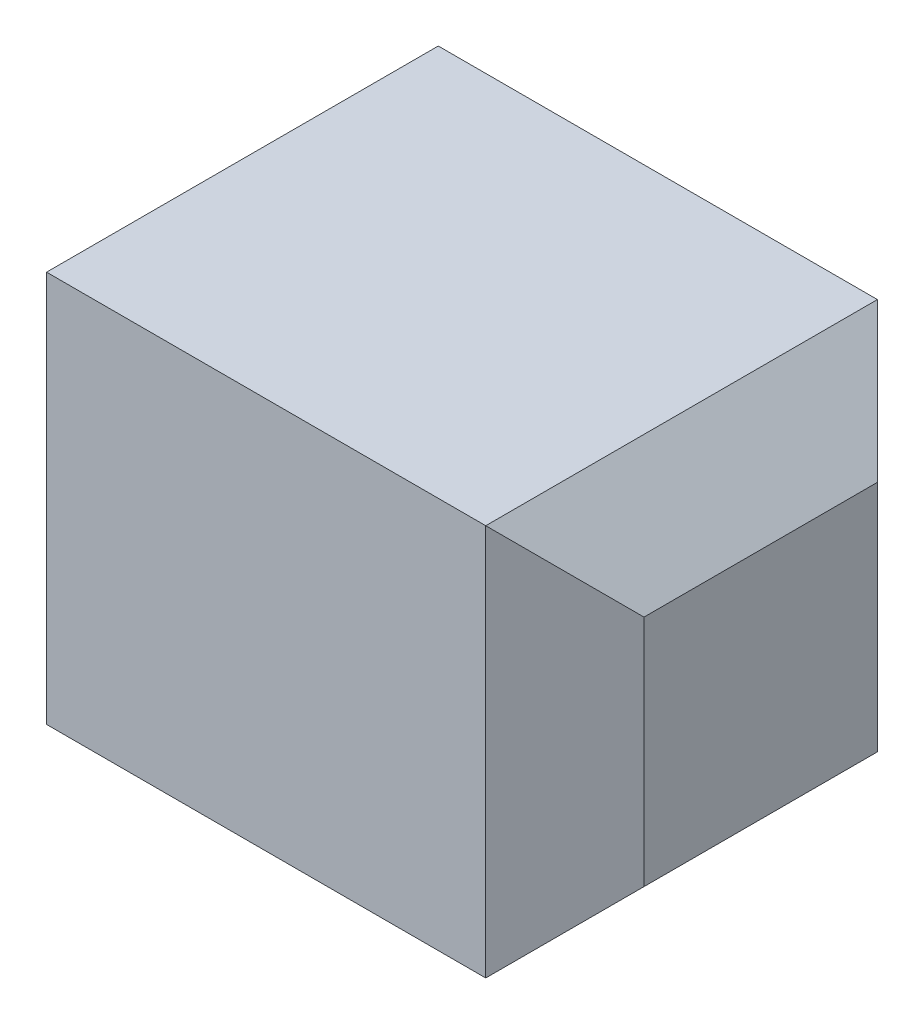
SolidWorks part; units mm, degrees
ref_plane "Front Plane" through (0, 0, 0) normal (0, 0, 1) x (1, 0, 0)
ref_plane "Top Plane" through (0, 0, 0) normal (0, 1, 0) x (1, 0, 0)
ref_plane "Right Plane" through (0, 0, 0) normal (1, 0, 0) x (0, 0, -1)
sketch "Sketch1" plane through (0, 0, 0) normal (1, 0, 0) x (0, 0, -1)
  line L1 (0, 0) -> (6.2865, 0)
  line L2 (0, 0) -> (0, 6.2865)
  line L3 (0, 6.2865) -> (6.2865, 6.2865)
  line L4 (6.2865, 0) -> (6.2865, 6.2865)
  dimension "D1" = 6.2865
extrude "Boss-Extrude1" add sketch "Sketch1" along normal blind 11.43 contours L3 L4 L1 L2
chamfer "Chamfer1" distance 1.27 angle 45 4 edges at (11.43, 6.2865, -3.1432) (11.43, 3.1432, -6.2865) (11.43, 0, -3.1432) (11.43, 3.1432, 0)
chamfer "Chamfer2" distance 3.1115 angle 45 4 edges at (0, 0, -3.1432) (0, 3.1432, -6.2865) (0, 6.2865, -3.1432) (0, 3.1432, 0)
